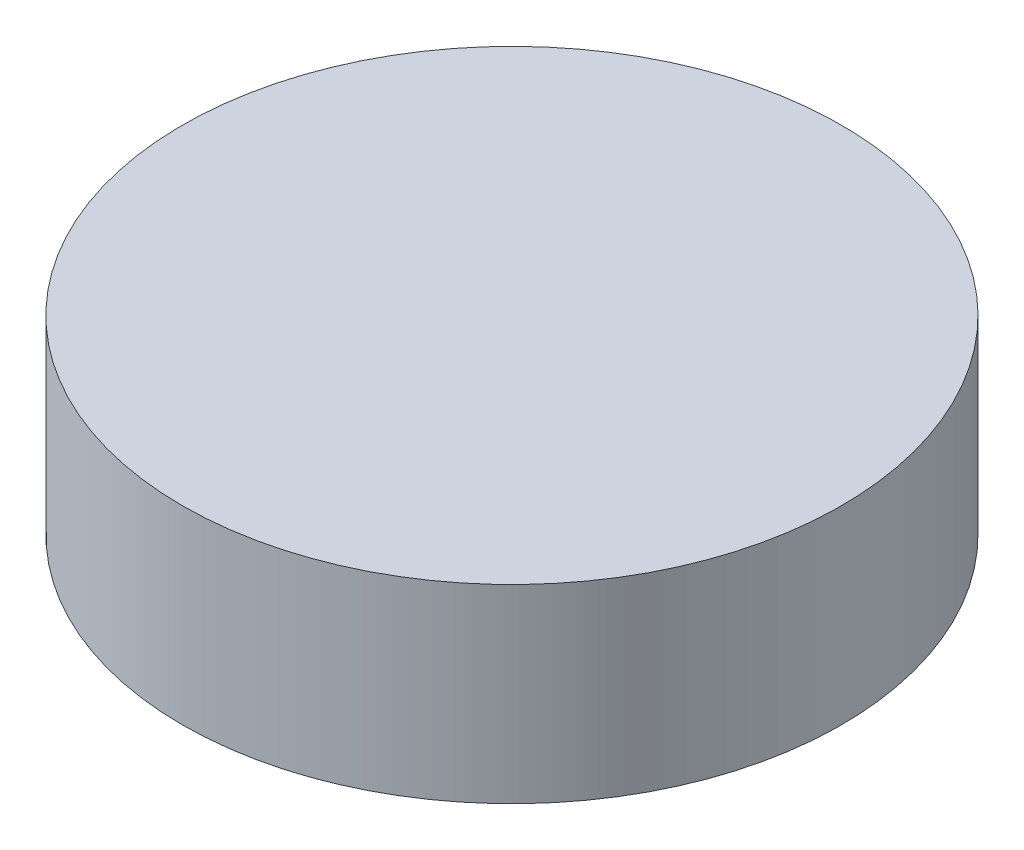
SolidWorks part; units mm, degrees
ref_plane "Front Plane" through (0, 0, 0) normal (0, 0, 1) x (1, 0, 0)
ref_plane "Top Plane" through (0, 0, 0) normal (0, 1, 0) x (1, 0, 0)
ref_plane "Right Plane" through (0, 0, 0) normal (1, 0, 0) x (0, 0, -1)
sketch "Sketch1" plane through (0, 0, 0) normal (0, 1, 0) x (1, 0, 0)
  circle A0 centre (0, 0) radius 7.9375
  dimension "D1" = 15.875
extrude "Boss-Extrude1" add sketch "Sketch1" along normal blind 4.572
